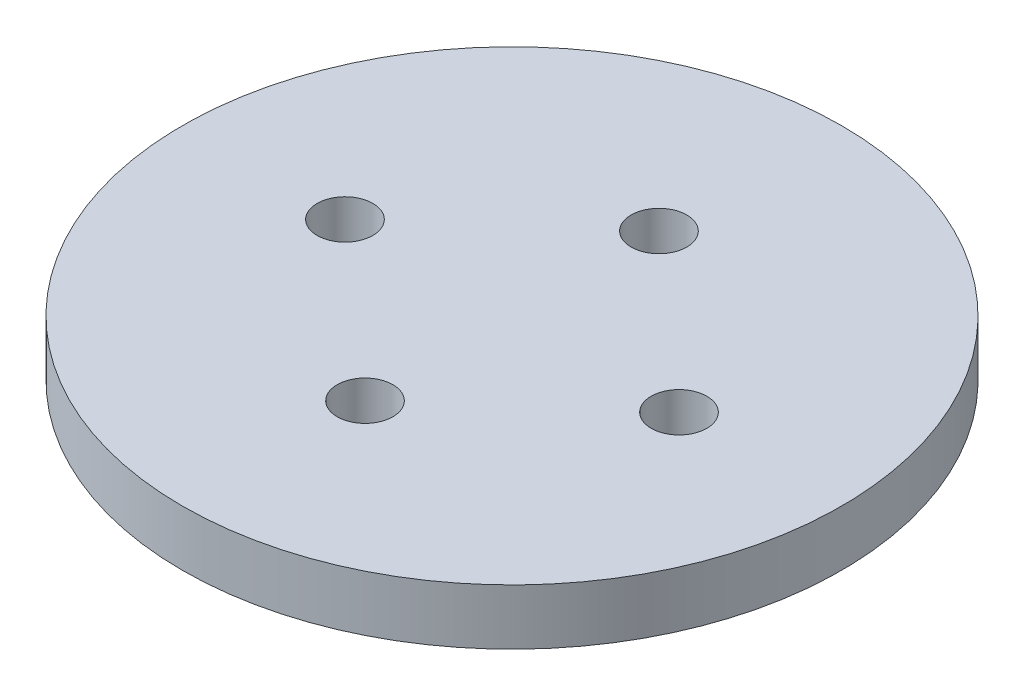
SolidWorks part; units mm, degrees
ref_plane "Front Plane" through (0, 0, 0) normal (0, 0, 1) x (1, 0, 0)
ref_plane "Top Plane" through (0, 0, 0) normal (0, 1, 0) x (1, 0, 0)
ref_plane "Right Plane" through (0, 0, 0) normal (1, 0, 0) x (0, 0, -1)
sketch "Sketch1" plane through (0, 0, 0) normal (0, 1, 0) x (1, 0, 0)
  circle A0 centre (0, 0) radius 37.592
  circle A1 centre (0, 16.764) radius 3.175
  circle A2 centre (0, -16.764) radius 3.175
  circle A3 centre (-19.05, 0) radius 3.175
  circle A4 centre (19.05, 0) radius 3.175
  dimension "D1" = 75.184
  dimension "D2" = 6.35
  dimension "D3" = 6.35
  dimension "D6" = 6.35
  dimension "D7" = 6.35
  dimension "D4" = 33.528
  dimension "D5" = 16.764
  dimension "D8" = 38.1
  dimension "D9" = 19.05
extrude "Boss-Extrude1" add sketch "Sketch1" along normal blind 6.35
